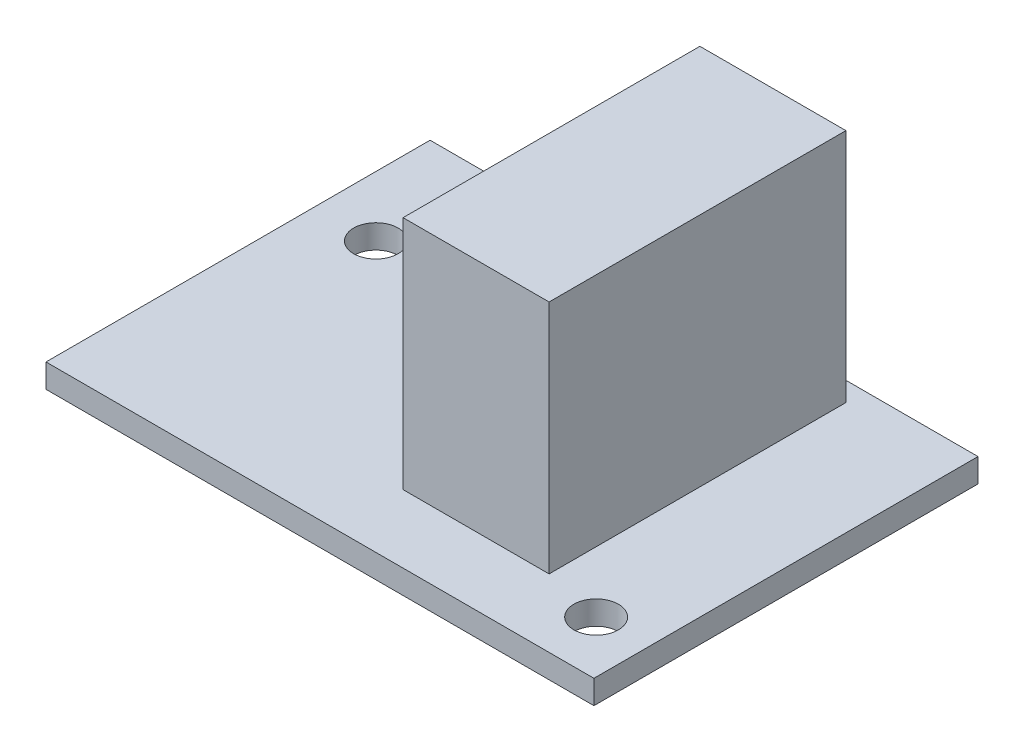
SolidWorks part; units mm, degrees
ref_plane "Front Plane" through (0, 0, 0) normal (0, 0, 1) x (1, 0, 0)
ref_plane "Top Plane" through (0, 0, 0) normal (0, 1, 0) x (1, 0, 0)
ref_plane "Right Plane" through (0, 0, 0) normal (1, 0, 0) x (0, 0, -1)
sketch "Sketch1" plane through (0, 0, 0) normal (0, 1, 0) x (1, 0, 0)
  line L1 (0, 0) -> (36.92, 0)
  line L2 (0, 0) -> (0, 25.88)
  line L3 (0, 25.88) -> (36.92, 25.88)
  line L4 (36.92, 0) -> (36.92, 25.88)
  circle A0 centre (33.42, 3.65) radius 1.5
  circle A1 centre (4.05, 18.18) radius 1.5
  dimension "D3" = 3.5
  dimension "D1" = 36.92
  dimension "D2" = 25.88
  dimension "D4" = 3.65
  dimension "D5" = 4.05
  dimension "D6" = 7.7
extrude "Boss-Extrude1" add sketch "Sketch1" along normal blind 1.6
sketch "Sketch2" plane through (0, 1.6, 0) normal (0, 1, 0) x (1, 0, 0)
  line L0 (36.92, 0) -> (36.92, 25.88) construction
  line L1 (19.48, 24.58) -> (29.32, 24.58)
  line L2 (19.48, 24.58) -> (19.48, 4.58)
  line L3 (19.48, 4.58) -> (29.32, 4.58)
  line L4 (29.32, 24.58) -> (29.32, 4.58)
  line L5 (36.92, 25.88) -> (0, 25.88) construction
  dimension "D1" = 20
  dimension "D2" = 9.84
  dimension "D3" = 7.6
  dimension "D4" = 1.3
extrude "Boss-Extrude2" add sketch "Sketch2" along normal blind 15.87
